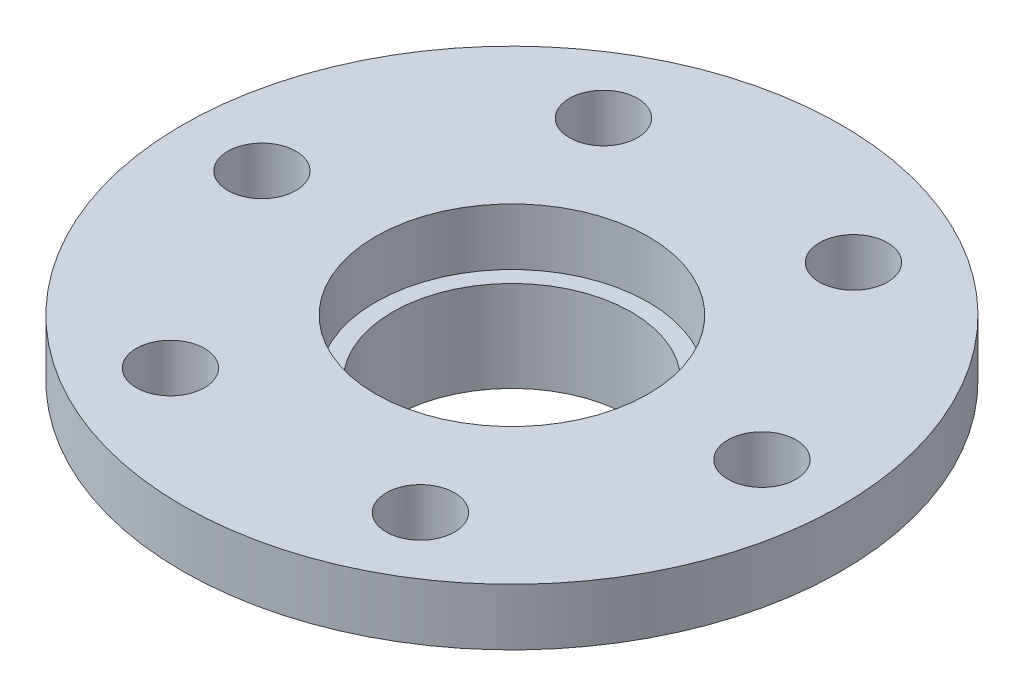
SolidWorks part; units mm, degrees
ref_plane "Front Plane" through (0, 0, 0) normal (0, 0, 1) x (1, 0, 0)
ref_plane "Top Plane" through (0, 0, 0) normal (0, 1, 0) x (1, 0, 0)
ref_plane "Right Plane" through (0, 0, 0) normal (1, 0, 0) x (0, 0, -1)
sketch "Sketch1" plane through (0, 0, 0) normal (0, 1, 0) x (1, 0, 0)
  circle A0 centre (0, 0) radius 17.5
  dimension "D1" = 35
extrude "Boss-Extrude1" add sketch "Sketch1" along normal blind 8
sketch "Sketch2" plane through (0, 8, 0) normal (0, 1, 0) x (1, 0, 0)
  circle A0 centre (0, 0) radius 29
  dimension "D1" = 58
extrude "Boss-Extrude2" add sketch "Sketch2" along normal blind 5
sketch "Sketch3" plane through (0, 13, 0) normal (0, 1, 0) x (1, 0, 0)
  circle A0 centre (0, 0) radius 12
  dimension "D1" = 24
extrude "Cut-Extrude1" cut sketch "Sketch3" against normal blind 5
sketch "Sketch4" plane through (0, 8, 0) normal (0, 1, 0) x (1, 0, 0)
  circle A3 centre (0, 0) radius 10.5
  circle A4 centre (0, 0) radius 10.5
  dimension "D1" = 1.5
extrude "Cut-Extrude2" cut sketch "Sketch4" against normal through all
sketch "Sketch5" plane through (0, 8, 0) normal (0, -1, 0) x (1, 0, 0)
  line L0 (0, 0) -> (22, 0) construction
  circle A0 centre (22, 0) radius 3
  circle A1 centre (11, -19.0526) radius 3
  circle A2 centre (-11, -19.0526) radius 3
  circle A3 centre (-22, 0) radius 3
  circle A4 centre (-11, 19.0526) radius 3
  circle A5 centre (11, 19.0526) radius 3
  point P16 (0, 0)
  dimension "D2" = 6
  dimension "D1" = 22
  dimension "D3" = 6
extrude "Cut-Extrude3" cut sketch "Sketch5" against normal up to next
sketch "Sketch6" plane through (0, 8, 0) normal (0, -1, 0) x (1, 0, 0)
  circle A0 centre (0, 0) radius 17.5 construction
  circle A1 centre (0, 0) radius 17.5
  circle A2 centre (0, 0) radius 18.8
  dimension "D1" = 1.3
extrude "Boss-Extrude3" add sketch "Sketch6" along normal blind 1
